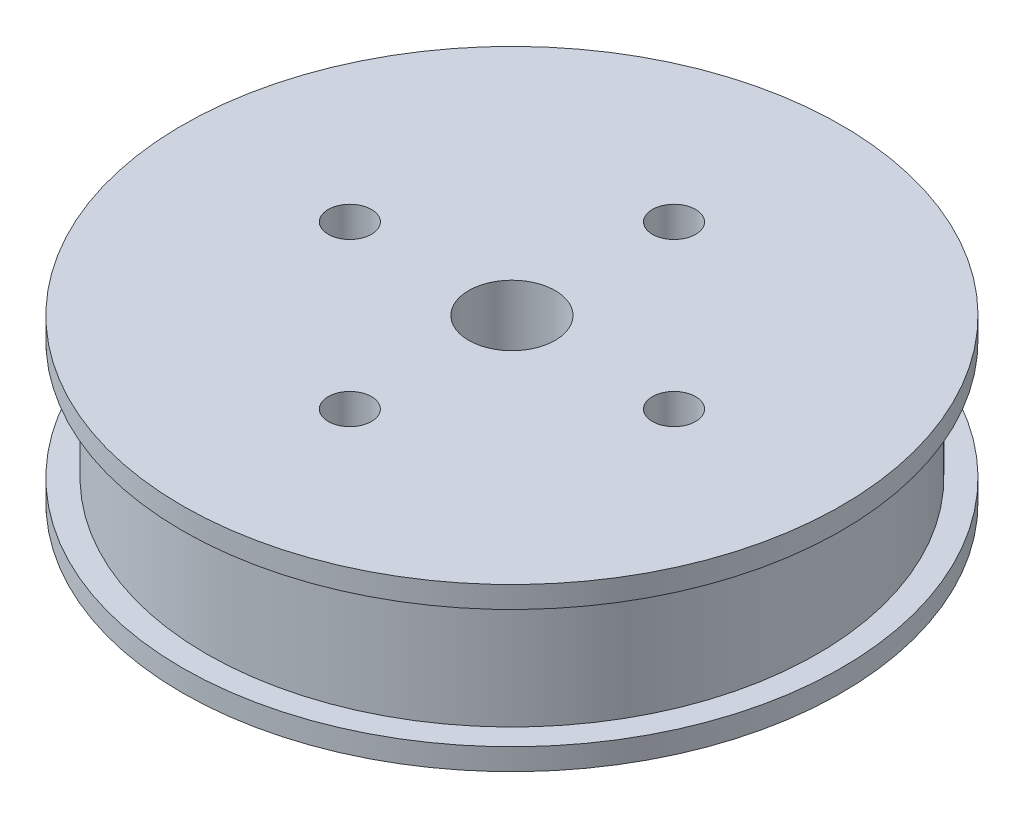
SolidWorks part; units mm, degrees
material "6061 合金"
ref_plane "Front" through (0, 0, 0) normal (0, 0, 1) x (1, 0, 0)
ref_plane "Top" through (0, 0, 0) normal (0, 1, 0) x (1, 0, 0)
ref_plane "Right" through (0, 0, 0) normal (1, 0, 0) x (0, 0, -1)
sketch "草图1" plane through (0, 0, 0) normal (0, 1, 0) x (1, 0, 0)
  circle A0 centre (0, 0) radius 30.5
  circle A1 centre (0, 0) radius 4
  circle A2 centre (0, 0) radius 15 construction
  circle A3 centre (0, 15) radius 2
  circle A4 centre (15, 0) radius 2
  circle A5 centre (0, -15) radius 2
  circle A6 centre (-15, 0) radius 2
  point P16 (0, 0)
  dimension "D1" = 61
  dimension "D2" = 8
  dimension "D3" = 4
  dimension "D4" = 30
  dimension "D5" = 4
extrude "凸台-拉伸1" add sketch "草图1" along normal blind 15
sketch "草图2" plane through (0, 0, 0) normal (0, 1, 0) x (1, 0, 0)
  circle A0 centre (0, 0) radius 28.265
  circle A1 centre (0, 0) radius 30.5
  dimension "D1" = 56.53
extrude "切除-拉伸1" cut sketch "草图2" along normal blind 11 from offset 2
